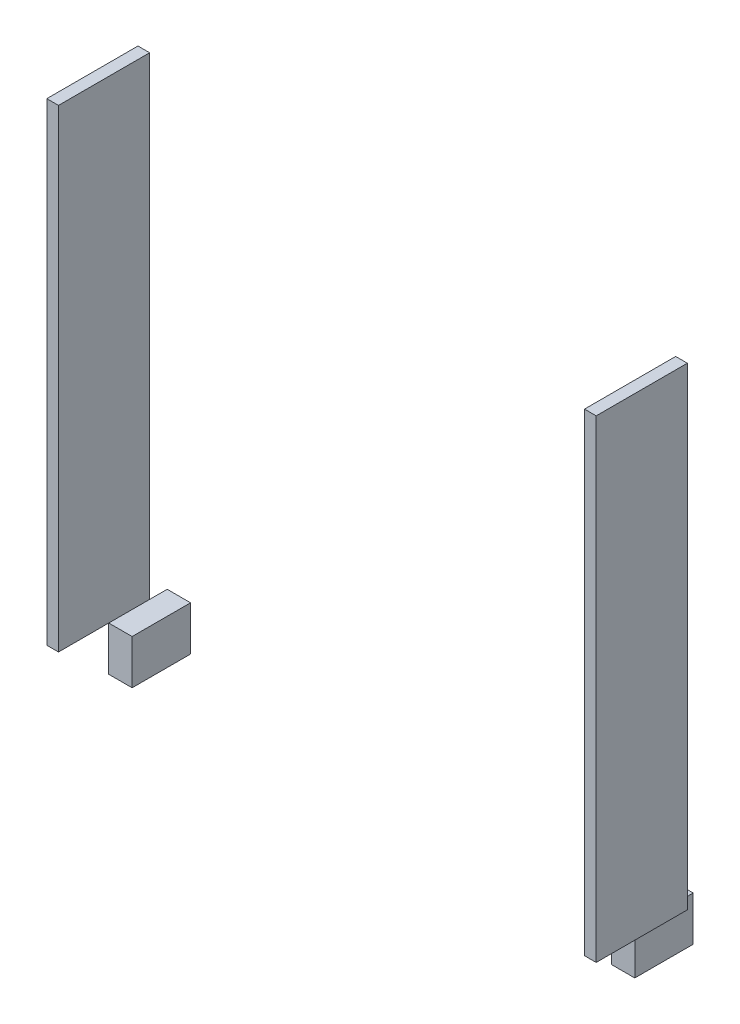
SolidWorks part; units mm, degrees
ref_plane "Front Plane" through (0, 0, 0) normal (0, 0, 1) x (1, 0, 0)
ref_plane "Top Plane" through (0, 0, 0) normal (0, 1, 0) x (1, 0, 0)
ref_plane "Right Plane" through (0, 0, 0) normal (1, 0, 0) x (0, 0, -1)
sketch "Sketch1" plane through (0, 0, 0) normal (0, 0, 1) x (1, 0, 0)
  line L1 (-235, 40) -> (-225, 40)
  line L2 (-235, 40) -> (-235, 445)
  line L3 (-235, 445) -> (-225, 445)
  line L4 (-225, 40) -> (-225, 445)
extrude "Wall_mount_rail_ASSUMED" add sketch "Sketch1" along normal blind 78 from offset 300 separate body
sketch "Sketch2" plane through (0, 0, 0) normal (0, 0, 1) x (1, 0, 0)
  line L1 (225, 40) -> (235, 40)
  line L2 (225, 40) -> (225, 445)
  line L3 (225, 445) -> (235, 445)
  line L4 (235, 40) -> (235, 445)
extrude "Boss-Extrude2" add sketch "Sketch2" along normal blind 78 from offset 300 separate body
sketch "Sketch3" plane through (0, 0, 0) normal (0, 0, 1) x (1, 0, 0)
  line L1 (-225, 2) -> (-205, 2)
  line L2 (-225, 2) -> (-225, 40)
  line L3 (-225, 40) -> (-205, 40)
  line L4 (-205, 2) -> (-205, 40)
extrude "Radiator_foot_ASSUMED" add sketch "Sketch3" along normal blind 50 from offset 285 separate body
sketch "Sketch4" plane through (0, 0, 0) normal (0, 0, 1) x (1, 0, 0)
  line L1 (205, 2) -> (225, 2)
  line L2 (205, 2) -> (205, 40)
  line L3 (205, 40) -> (225, 40)
  line L4 (225, 2) -> (225, 40)
extrude "Boss-Extrude4" add sketch "Sketch4" along normal blind 50 from offset 285 separate body
